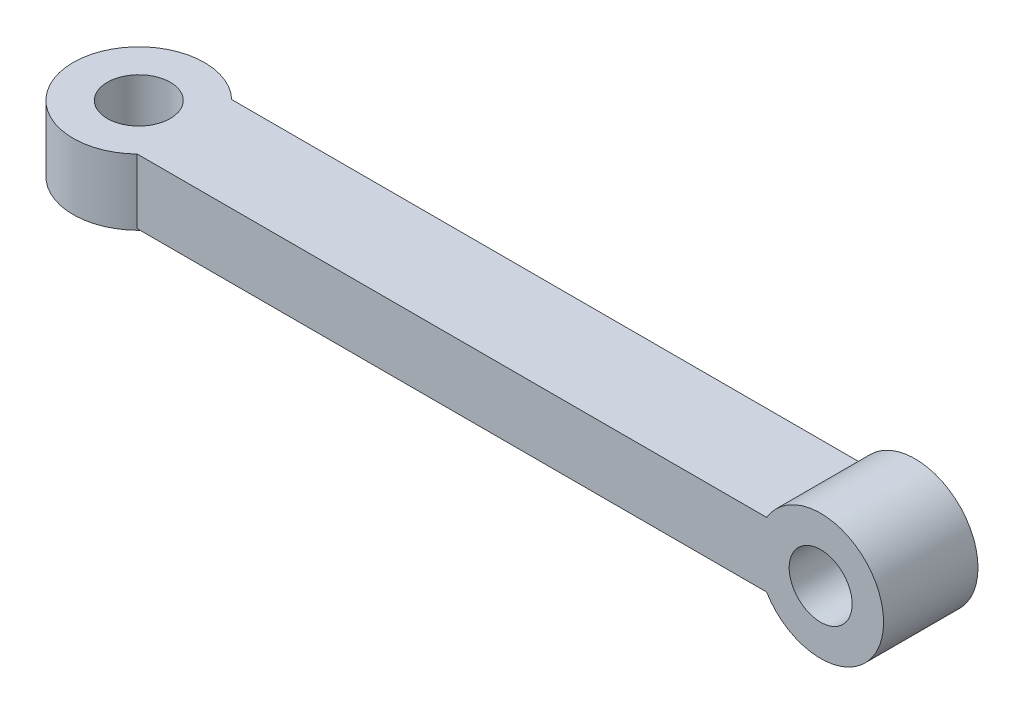
SolidWorks part; units mm, degrees
ref_plane "Front Plane" through (0, 0, 0) normal (0, 0, 1) x (1, 0, 0)
ref_plane "Top Plane" through (0, 0, 0) normal (0, 1, 0) x (1, 0, 0)
ref_plane "Right Plane" through (0, 0, 0) normal (1, 0, 0) x (0, 0, -1)
sketch "Sketch4" plane through (0, 0, 0) normal (0, 0, 1) x (1, 0, 0)
  line L0 (101.6892, -7.1452) -> (1.6892, -7.1452)
  line L1 (101.6892, 3.1254) -> (1.6892, 3.1254)
  line L2 (1.6892, -7.1452) -> (1.6892, 3.1254)
  arc A0 (101.6892, 3.1254) -> (101.6892, -7.1452) centre (110.2699, -2.0099) cw
  circle A1 centre (110.2699, -2.0099) radius 5
extrude "Boss-Extrude6" add sketch "Sketch4" along normal blind 15
sketch "Sketch9" plane through (0, 3.1254, 0) normal (0, 1, 0) x (1, 0, 0)
  circle A0 centre (-5.566, -7.5) radius 10.4349
  circle A1 centre (-5.566, -7.5) radius 5
extrude "Boss-Extrude8" add sketch "Sketch9" against normal blind 10.5
